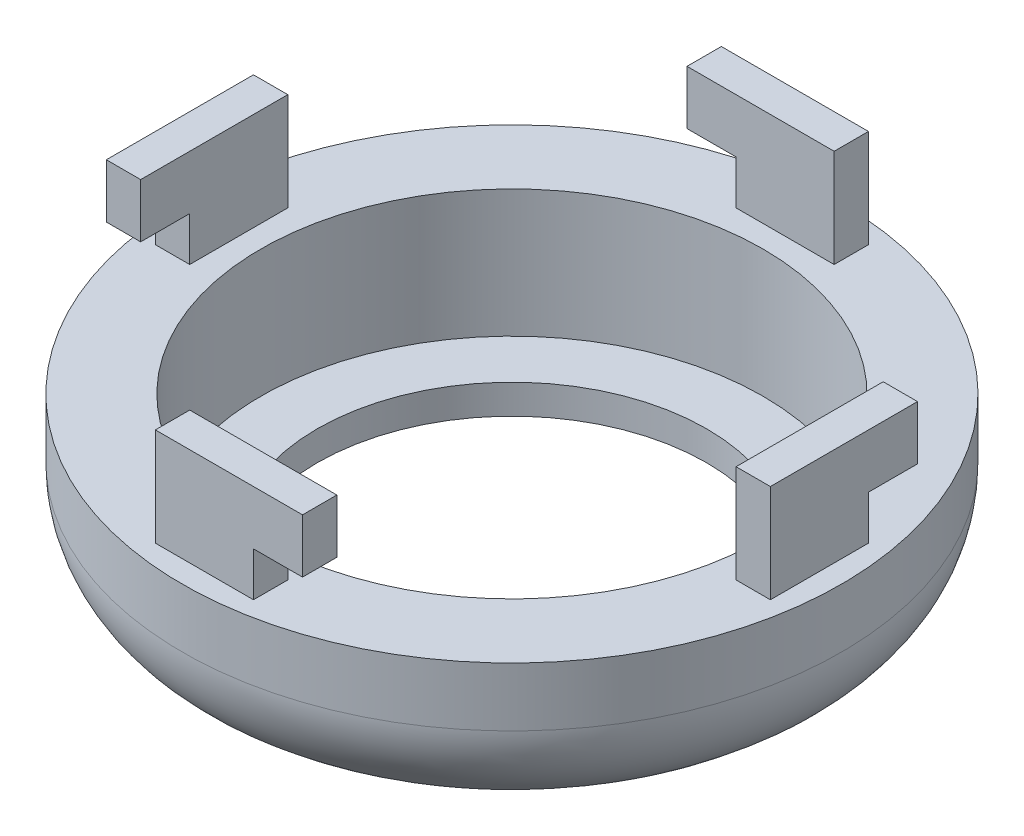
SolidWorks part; units mm, degrees
ref_plane "Front Plane" through (0, 0, 0) normal (0, 0, 1) x (1, 0, 0)
ref_plane "Top Plane" through (0, 0, 0) normal (0, 1, 0) x (1, 0, 0)
ref_plane "Right Plane" through (0, 0, 0) normal (1, 0, 0) x (0, 0, -1)
sketch "Sketch1" plane through (0, 0, 0) normal (0, 1, 0) x (1, 0, 0)
  circle A0 centre (0, 0) radius 25.6
  circle A1 centre (0, 0) radius 33.6
  dimension "D1" = 51.2
  dimension "D2" = 8
extrude "Boss-Extrude1" add sketch "Sketch1" along normal blind 13
sketch "Sketch2" plane through (0, 13, 0) normal (0, 1, 0) x (1, 0, 0)
  line L14 (-5, -31.35) -> (5, -31.35)
  line L15 (5, -31.35) -> (5, -27.85)
  line L16 (-5, -27.85) -> (5, -27.85)
  line L17 (-5, -31.35) -> (-5, -27.85)
extrude "Boss-Extrude2" add sketch "Sketch2" along normal blind 10
sketch "Sketch3" plane through (0, 0, 0) normal (0, -1, 0) x (1, 0, 0)
  circle A0 centre (0, 0) radius 33.6
  circle A1 centre (0, 0) radius 19.85
  dimension "D1" = 39.7
extrude "Boss-Extrude3" add sketch "Sketch3" along normal blind 3
sketch "Sketch4" plane through (0, 0, 31.35) normal (0, 0, 1) x (1, 0, 0)
  line L1 (-5, 23) -> (10, 23)
  line L2 (-5, 23) -> (-5, 17.5)
  line L3 (-5, 17.5) -> (10, 17.5)
  line L4 (10, 23) -> (10, 17.5)
  dimension "D1" = 5.5
  dimension "D2" = 15
extrude "Boss-Extrude4" add sketch "Sketch4" against normal blind 3.5
pattern_circular "CirPattern1" count 4 over 360 about axis through (0, 0, 0) along (0, 1, 0) of "Boss-Extrude2", "Boss-Extrude4"
ref_plane "Plane1" through (0, 15, 0) normal (0, 1, 0) x (1, 0, 0)
fillet "Fillet1" radius 10 1 edges at (0, -3, -33.6)
